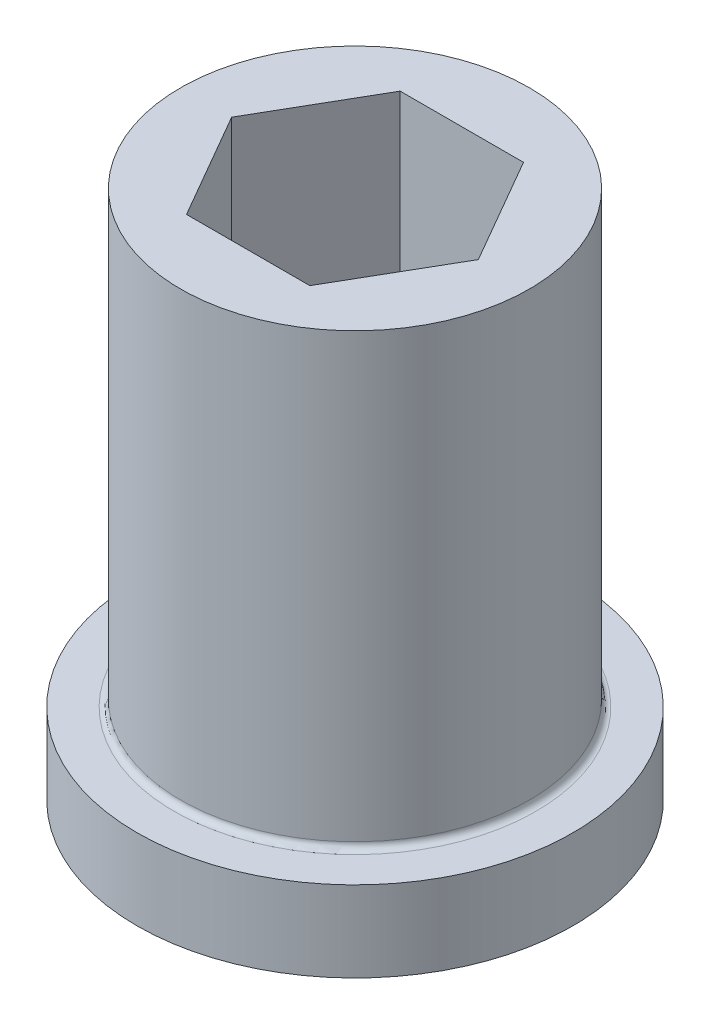
SolidWorks part; units mm, degrees
ref_plane "Front Plane" through (0, 0, 0) normal (0, 0, 1) x (1, 0, 0)
ref_plane "Top Plane" through (0, 0, 0) normal (0, 1, 0) x (1, 0, 0)
ref_plane "Right Plane" through (0, 0, 0) normal (1, 0, 0) x (0, 0, -1)
sketch "Sketch1" plane through (0, 0, 0) normal (0, 1, 0) x (1, 0, 0)
  line L1 (2.829, 0) -> (1.4145, 2.45)
  line L2 (1.4145, 2.45) -> (-1.4145, 2.45)
  line L3 (-1.4145, 2.45) -> (-2.829, 0)
  line L4 (-2.829, 0) -> (-1.4145, -2.45)
  line L5 (-1.4145, -2.45) -> (1.4145, -2.45)
  line L6 (1.4145, -2.45) -> (2.829, 0)
  circle A0 centre (0, 0) radius 4
  circle A1 centre (0, 0) radius 2.45 construction
  dimension "D1" = 4.9
  dimension "D2" = 8
extrude "Boss-Extrude1" add sketch "Sketch1" along normal blind 10.3
sketch "Sketch2" plane through (0, 0, 0) normal (0, -1, 0) x (1, 0, 0)
  line L1 (2.829, 0) -> (1.4145, 2.45)
  line L2 (1.4145, 2.45) -> (-1.4145, 2.45)
  line L3 (-1.4145, 2.45) -> (-2.829, 0)
  line L4 (-2.829, 0) -> (-1.4145, -2.45)
  line L5 (-1.4145, -2.45) -> (1.4145, -2.45)
  line L6 (1.4145, -2.45) -> (2.829, 0)
  circle A0 centre (0, 0) radius 5
  circle A1 centre (0, 0) radius 2.45 construction
  dimension "D1" = 10
  dimension "D2" = 4.9
extrude "Boss-Extrude2" add sketch "Sketch2" along normal blind 1.85
fillet "Fillet1" radius 0.15 1 edges at (0, 0, 4)
